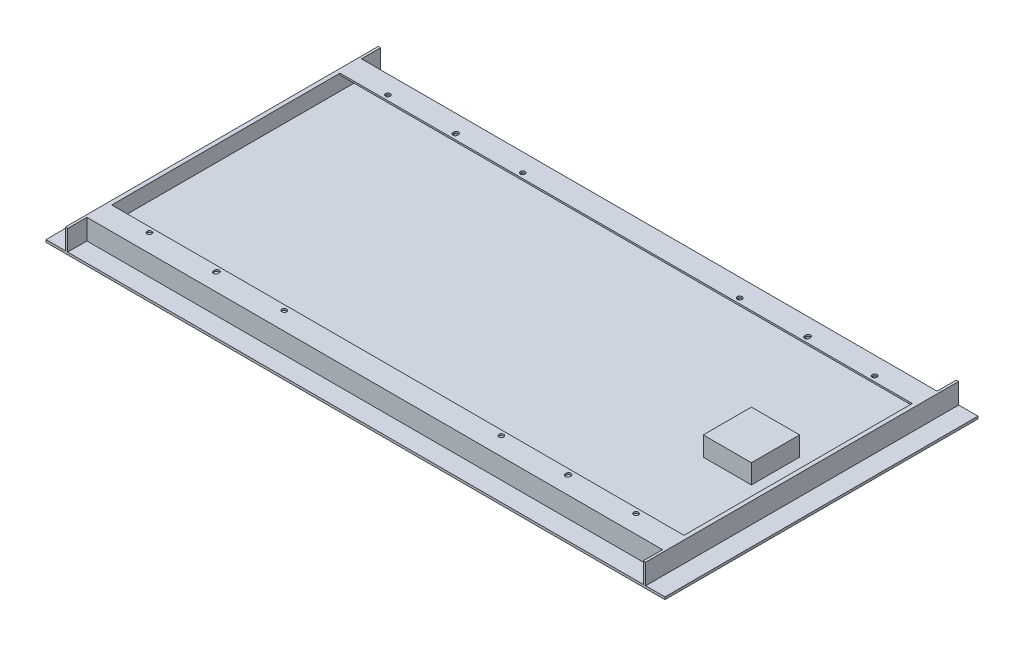
SolidWorks part; units mm, degrees
ref_plane "Front Plane" through (0, 0, 0) normal (0, 0, 1) x (1, 0, 0)
ref_plane "Top Plane" through (0, 0, 0) normal (0, 1, 0) x (1, 0, 0)
ref_plane "Right Plane" through (0, 0, 0) normal (1, 0, 0) x (0, 0, -1)
sketch "Sketch1" plane through (0, 0, 0) normal (0, 1, 0) x (1, 0, 0)
  line L1 (-377.19, 175.5775) -> (377.19, 175.5775)
  line L2 (-377.19, 175.5775) -> (-377.19, -175.5775)
  line L3 (-377.19, -175.5775) -> (377.19, -175.5775)
  line L4 (377.19, 175.5775) -> (377.19, -175.5775)
  line L5 (-377.19, 175.5775) -> (377.19, -175.5775) construction
  line L6 (-377.19, -175.5775) -> (377.19, 175.5775) construction
  point P0 (0, 0)
  dimension "D1" = 754.38
  dimension "D2" = 351.155
extrude "Boss-Extrude1" add sketch "Sketch1" along normal blind 9.525
sketch "Sketch5" plane through (-377.19, 0, 0) normal (-1, 0, 0) x (0, 0, 1)
  line L0 (-175.5775, 9.525) -> (-175.5775, 0) construction
  line L1 (-177.8, 0) -> (177.8, 0)
  line L2 (-177.8, 0) -> (-177.8, 30.1625)
  line L3 (-177.8, 30.1625) -> (177.8, 30.1625)
  line L4 (177.8, 0) -> (177.8, 30.1625)
  dimension "D1" = 355.6
  dimension "D2" = 2.2225
  dimension "D3" = 30.1625
extrude "Boss-Extrude4" add sketch "Sketch5" along normal blind 2.2225
sketch "Sketch6" plane through (0, 0, 175.5775) normal (0, 0, 1) x (1, 0, 0)
  line L1 (-377.19, 0) -> (377.19, 0)
  line L2 (-377.19, 0) -> (-377.19, 30.1625)
  line L3 (-377.19, 30.1625) -> (377.19, 30.1625)
  line L4 (377.19, 0) -> (377.19, 30.1625)
  dimension "D1" = 30.1625
extrude "Boss-Extrude5" add sketch "Sketch6" along normal blind 2.2225
sketch "Sketch8" plane through (0, 0, -175.5775) normal (0, 0, -1) x (-1, 0, 0)
  line L1 (377.19, 0) -> (-377.19, 0)
  line L2 (377.19, 0) -> (377.19, 30.1625)
  line L3 (377.19, 30.1625) -> (-377.19, 30.1625)
  line L4 (-377.19, 0) -> (-377.19, 30.1625)
  dimension "D1" = 30.1625
extrude "Boss-Extrude6" add sketch "Sketch8" along normal blind 2.2225
sketch "Sketch14" plane through (377.19, 0, 0) normal (1, 0, 0) x (0, 0, -1)
  line L1 (-177.8, 0) -> (177.8, 0)
  line L2 (-177.8, 0) -> (-177.8, 30.1625)
  line L3 (-177.8, 30.1625) -> (177.8, 30.1625)
  line L4 (177.8, 0) -> (177.8, 30.1625)
extrude "Boss-Extrude7" add sketch "Sketch14" along normal blind 2.2225
sketch "Sketch16" plane through (0, 0, -175.5775) normal (0, 0, 1) x (1, 0, 0)
  line L0 (-377.19, 9.525) -> (-377.19, 30.1625) construction
  line L1 (377.19, 30.1625) -> (-377.19, 30.1625)
  line L2 (377.19, 30.1625) -> (377.19, 27.94)
  line L3 (377.19, 27.94) -> (-377.19, 27.94)
  line L4 (-377.19, 30.1625) -> (-377.19, 27.94)
  dimension "D1" = 2.2225
extrude "Boss-Extrude8" add sketch "Sketch16" along normal blind 25.0825
sketch "Sketch17" plane through (0, 0, 175.5775) normal (0, 0, -1) x (-1, 0, 0)
  line L0 (377.19, 30.1625) -> (377.19, 9.525) construction
  line L1 (-377.19, 30.1625) -> (377.19, 30.1625)
  line L2 (-377.19, 30.1625) -> (-377.19, 27.94)
  line L3 (-377.19, 27.94) -> (377.19, 27.94)
  line L4 (377.19, 30.1625) -> (377.19, 27.94)
  dimension "D1" = 2.2225
extrude "Boss-Extrude9" add sketch "Sketch17" along normal blind 25.0825
sketch "Sketch19" plane through (0, 30.1625, 0) normal (0, 1, 0) x (1, 0, 0)
  line L0 (-228.727, 157.1625) -> (-228.727, 158.4325)
  line L1 (-379.4125, -177.8) -> (-379.4125, 177.8) construction
  line L2 (-235.077, 158.4325) -> (-235.077, 157.1625)
  line L3 (377.19, 150.495) -> (-377.19, 150.495) construction
  line L4 (379.4125, 0) -> (-379.4125, 0) construction
  line L5 (379.4125, 177.8) -> (379.4125, -177.8) construction
  line L6 (0, -177.8) -> (0, 177.8) construction
  line L7 (-379.4125, -177.8) -> (379.4125, -177.8) construction
  line L8 (-379.4125, 177.8) -> (379.4125, 177.8) construction
  line L9 (-235.077, -158.4325) -> (-235.077, -157.1625)
  line L10 (-228.727, -157.1625) -> (-228.727, -158.4325)
  line L11 (228.727, -157.1625) -> (228.727, -158.4325)
  line L12 (235.077, -158.4325) -> (235.077, -157.1625)
  line L13 (228.727, 157.1625) -> (228.727, 158.4325)
  line L14 (235.077, 158.4325) -> (235.077, 157.1625)
  arc A0 (-235.077, 157.1625) -> (-228.727, 157.1625) centre (-231.902, 157.1625) ccw
  arc A1 (-228.727, 158.4325) -> (-235.077, 158.4325) centre (-231.902, 158.4325) ccw
  arc A2 (-228.727, -158.4325) -> (-235.077, -158.4325) centre (-231.902, -158.4325) cw
  arc A3 (-235.077, -157.1625) -> (-228.727, -157.1625) centre (-231.902, -157.1625) cw
  arc A4 (235.077, -157.1625) -> (228.727, -157.1625) centre (231.902, -157.1625) ccw
  arc A5 (228.727, -158.4325) -> (235.077, -158.4325) centre (231.902, -158.4325) ccw
  arc A6 (235.077, 157.1625) -> (228.727, 157.1625) centre (231.902, 157.1625) cw
  arc A7 (228.727, 158.4325) -> (235.077, 158.4325) centre (231.902, 158.4325) cw
  dimension "D1" = 6.35
  dimension "D4" = 6.6675
  dimension "D2" = 1.27
  dimension "D3" = 144.3355
extrude "Cut-Extrude1" cut sketch "Sketch19" against normal blind 2.2225
sketch "Sketch21" plane through (0, 30.1625, 0) normal (0, 1, 0) x (1, 0, 0)
  line L0 (0, 0) -> (-348.6246, 0) construction
  line L1 (-231.902, -161.6075) -> (-231.902, -81.1596) construction
  line L2 (0, -177.8) -> (0, 177.8) construction
  line L3 (-379.4125, -177.8) -> (379.4125, -177.8) construction
  line L4 (-379.4125, 177.8) -> (379.4125, 177.8) construction
  circle A0 centre (-143.002, -157.1625) radius 3.175
  arc A1 (-228.727, -157.1625) -> (-235.077, -157.1625) centre (-231.902, -157.1625) ccw construction
  circle A2 centre (-143.002, 157.1625) radius 3.175
  arc A3 (-235.077, -158.4325) -> (-228.727, -158.4325) centre (-231.902, -158.4325) ccw construction
  circle A4 centre (-320.802, -157.1625) radius 3.175
  circle A5 centre (-320.802, 157.1625) radius 3.175
  circle A6 centre (143.002, 157.1625) radius 3.175
  circle A7 centre (320.802, 157.1625) radius 3.175
  circle A8 centre (143.002, -157.1625) radius 3.175
  circle A9 centre (320.802, -157.1625) radius 3.175
  dimension "D1" = 6.35
  dimension "D2" = 88.9
extrude "Cut-Extrude3" cut sketch "Sketch21" against normal up to surface (2.2225 mm away) up to face at (231.902, 27.94, 157.7975)
sketch "Sketch22" plane through (0, 0, 177.8) normal (0, 0, 1) x (1, 0, 0)
  line L1 (-379.4125, 0) -> (379.4125, 0)
  line L2 (-379.4125, 0) -> (-379.4125, 30.1625)
  line L3 (-379.4125, 30.1625) -> (379.4125, 30.1625)
  line L4 (379.4125, 0) -> (379.4125, 30.1625)
extrude "Boss-Extrude10" add sketch "Sketch22" along normal blind 3.175
sketch "Sketch23" plane through (0, 0, 180.975) normal (0, 0, 1) x (1, 0, 0)
  line L0 (379.4125, 0) -> (379.4125, 30.1625) construction
  line L1 (-379.4125, 0) -> (379.4125, 0)
  line L2 (-379.4125, 0) -> (-379.4125, 3.175)
  line L3 (-379.4125, 3.175) -> (379.4125, 3.175)
  line L4 (379.4125, 0) -> (379.4125, 3.175)
  dimension "D1" = 3.175
extrude "Boss-Extrude11" add sketch "Sketch23" along normal blind 25.4
sketch "Sketch24" plane through (0, 0, -177.8) normal (0, 0, -1) x (-1, 0, 0)
  line L1 (-379.4125, 0) -> (379.4125, 0)
  line L2 (-379.4125, 0) -> (-379.4125, 30.1625)
  line L3 (-379.4125, 30.1625) -> (379.4125, 30.1625)
  line L4 (379.4125, 0) -> (379.4125, 30.1625)
extrude "Boss-Extrude12" add sketch "Sketch24" along normal blind 3.175
sketch "Sketch25" plane through (0, 0, -180.975) normal (0, 0, -1) x (-1, 0, 0)
  line L0 (379.4125, 0) -> (379.4125, 30.1625) construction
  line L1 (-379.4125, 0) -> (379.4125, 0)
  line L2 (-379.4125, 0) -> (-379.4125, 3.175)
  line L3 (-379.4125, 3.175) -> (379.4125, 3.175)
  line L4 (379.4125, 0) -> (379.4125, 3.175)
  dimension "D1" = 3.175
extrude "Boss-Extrude13" add sketch "Sketch25" along normal blind 25.4
sketch "Sketch26" plane through (-379.4125, 0, 0) normal (-1, 0, 0) x (0, 0, 1)
  line L2 (206.375, 30.1625) -> (-206.375, 30.1625)
  line L3 (206.375, 30.1625) -> (206.375, 0)
  line L4 (206.375, 0) -> (-206.375, 0)
  line L5 (-206.375, 30.1625) -> (-206.375, 0)
extrude "Boss-Extrude14" add sketch "Sketch26" along normal blind 3.175
sketch "Sketch27" plane through (-382.5875, 0, 0) normal (-1, 0, 0) x (0, 0, 1)
  line L1 (-206.375, 30.1625) -> (-206.375, 0) construction
  line L2 (206.375, 0) -> (-206.375, 0)
  line L3 (206.375, 0) -> (206.375, 3.175)
  line L4 (206.375, 3.175) -> (-206.375, 3.175)
  line L5 (-206.375, 0) -> (-206.375, 3.175)
  dimension "D1" = 3.175
extrude "Boss-Extrude15" add sketch "Sketch27" along normal blind 25.4
sketch "Sketch28" plane through (379.4125, 0, 0) normal (1, 0, 0) x (0, 0, -1)
  line L2 (206.375, 30.1625) -> (-206.375, 30.1625)
  line L3 (206.375, 30.1625) -> (206.375, 0)
  line L4 (206.375, 0) -> (-206.375, 0)
  line L5 (-206.375, 30.1625) -> (-206.375, 0)
extrude "Boss-Extrude16" add sketch "Sketch28" along normal blind 3.175
sketch "Sketch29" plane through (382.5875, 0, 0) normal (1, 0, 0) x (0, 0, -1)
  line L1 (-206.375, 30.1625) -> (-206.375, 0) construction
  line L2 (206.375, 0) -> (-206.375, 0)
  line L3 (206.375, 0) -> (206.375, 3.175)
  line L4 (206.375, 3.175) -> (-206.375, 3.175)
  line L5 (-206.375, 0) -> (-206.375, 3.175)
  dimension "D1" = 3.175
extrude "Boss-Extrude17" add sketch "Sketch29" along normal blind 25.4
sketch "Sketch30" plane through (0, 9.525, 0) normal (0, 1, 0) x (1, 0, 0)
  line L0 (377.19, 150.495) -> (377.19, -150.495) construction
  line L1 (343.535, 35.6115) -> (280.035, 35.6115)
  line L2 (343.535, 35.6115) -> (343.535, -27.8885)
  line L3 (343.535, -27.8885) -> (280.035, -27.8885)
  line L4 (280.035, 35.6115) -> (280.035, -27.8885)
  line L5 (343.535, 35.6115) -> (280.035, -27.8885) construction
  line L6 (343.535, -27.8885) -> (280.035, 35.6115) construction
  point P0 (311.785, 3.8615)
  dimension "D1" = 63.5
  dimension "D2" = 63.5
  dimension "D3" = 33.655
extrude "Boss-Extrude18" add sketch "Sketch30" along normal blind 25.4
